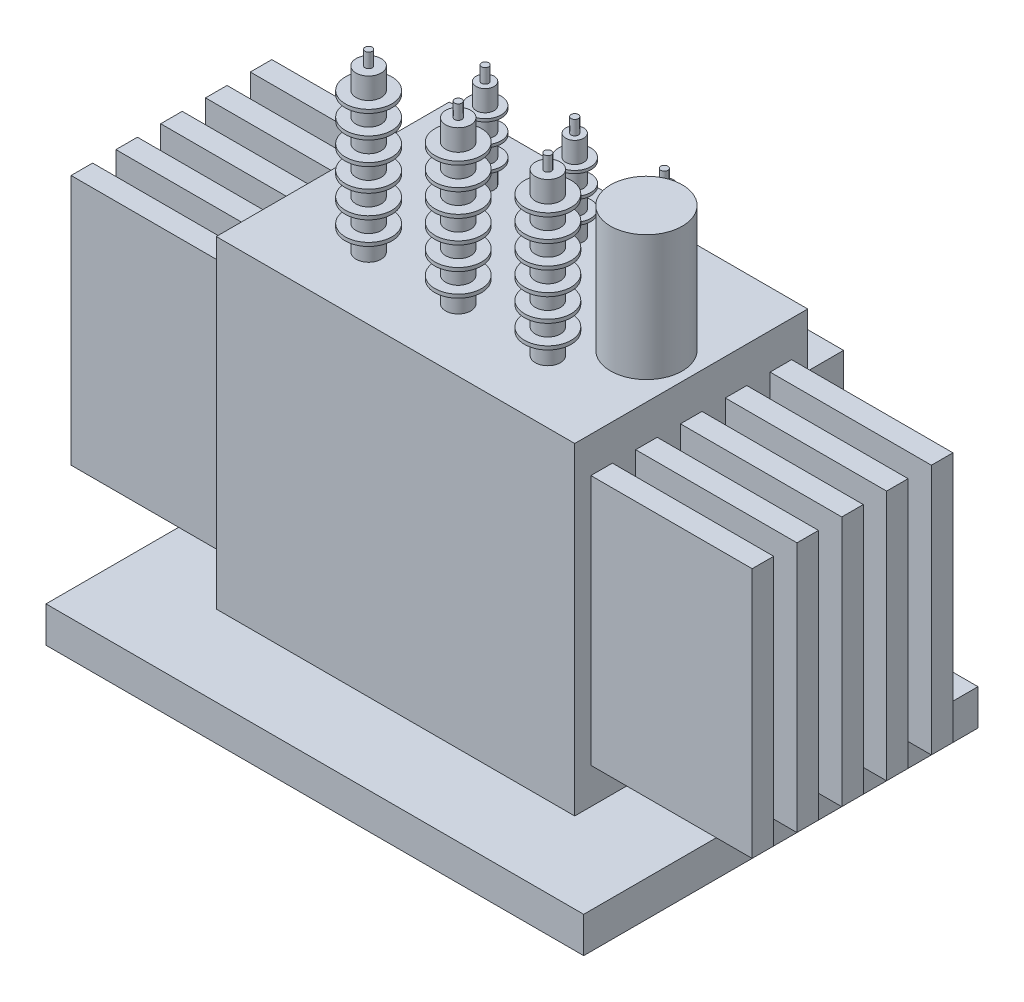
SolidWorks part; units mm, degrees
ref_plane "Front Plane" through (0, 0, 0) normal (0, 0, 1) x (1, 0, 0)
ref_plane "Top Plane" through (0, 0, 0) normal (0, 1, 0) x (1, 0, 0)
ref_plane "Right Plane" through (0, 0, 0) normal (1, 0, 0) x (0, 0, -1)
sketch "Sketch1" plane through (0, 0, 0) normal (0, 1, 0) x (1, 0, 0)
  line L1 (-1500, -1100) -> (1500, -1100)
  line L2 (-1500, -1100) -> (-1500, 1100)
  line L3 (-1500, 1100) -> (1500, 1100)
  line L4 (1500, -1100) -> (1500, 1100)
  line L5 (-1500, -1100) -> (1500, 1100) construction
  line L6 (-1500, 1100) -> (1500, -1100) construction
  point P0 (0, 0)
extrude "Pad" add sketch "Sketch1" along normal blind 200 separate body
sketch "Sketch2" plane through (0, 0, 0) normal (0, 1, 0) x (1, 0, 0)
  line L1 (-1000, -650) -> (1000, -650)
  line L2 (-1000, -650) -> (-1000, 650)
  line L3 (-1000, 650) -> (1000, 650)
  line L4 (1000, -650) -> (1000, 650)
  line L5 (-1000, -650) -> (1000, 650) construction
  line L6 (-1000, 650) -> (1000, -650) construction
  point P0 (0, 0)
extrude "Main tank" add sketch "Sketch2" along normal blind 1800 from offset 200 separate body
sketch "Sketch3" plane through (0, 0, 0) normal (0, 1, 0) x (1, 0, 0)
  line L1 (1000, 440) -> (1900, 440)
  line L2 (1000, 440) -> (1000, 560)
  line L3 (1000, 560) -> (1900, 560)
  line L4 (1900, 440) -> (1900, 560)
  line L5 (1000, 440) -> (1900, 560) construction
  line L6 (1000, 560) -> (1900, 440) construction
  point P0 (1450, 500)
extrude "Radiator +x 1" add sketch "Sketch3" along normal blind 1400 from offset 400 separate body
sketch "Sketch4" plane through (0, 0, 0) normal (0, 1, 0) x (1, 0, 0)
  line L1 (-1900, 440) -> (-1000, 440)
  line L2 (-1900, 440) -> (-1900, 560)
  line L3 (-1900, 560) -> (-1000, 560)
  line L4 (-1000, 440) -> (-1000, 560)
  line L5 (-1900, 440) -> (-1000, 560) construction
  line L6 (-1900, 560) -> (-1000, 440) construction
  point P0 (-1450, 500)
extrude "Radiator -x 1" add sketch "Sketch4" along normal blind 1400 from offset 400 separate body
sketch "Sketch5" plane through (0, 0, 0) normal (0, 1, 0) x (1, 0, 0)
  line L1 (1000, 190) -> (1900, 190)
  line L2 (1000, 190) -> (1000, 310)
  line L3 (1000, 310) -> (1900, 310)
  line L4 (1900, 190) -> (1900, 310)
  line L5 (1000, 190) -> (1900, 310) construction
  line L6 (1000, 310) -> (1900, 190) construction
  point P0 (1450, 250)
extrude "Radiator +x 2" add sketch "Sketch5" along normal blind 1400 from offset 400 separate body
sketch "Sketch6" plane through (0, 0, 0) normal (0, 1, 0) x (1, 0, 0)
  line L1 (-1900, 190) -> (-1000, 190)
  line L2 (-1900, 190) -> (-1900, 310)
  line L3 (-1900, 310) -> (-1000, 310)
  line L4 (-1000, 190) -> (-1000, 310)
  line L5 (-1900, 190) -> (-1000, 310) construction
  line L6 (-1900, 310) -> (-1000, 190) construction
  point P0 (-1450, 250)
extrude "Radiator -x 2" add sketch "Sketch6" along normal blind 1400 from offset 400 separate body
sketch "Sketch7" plane through (0, 0, 0) normal (0, 1, 0) x (1, 0, 0)
  line L1 (1000, -60) -> (1900, -60)
  line L2 (1000, -60) -> (1000, 60)
  line L3 (1000, 60) -> (1900, 60)
  line L4 (1900, -60) -> (1900, 60)
  line L5 (1000, -60) -> (1900, 60) construction
  line L6 (1000, 60) -> (1900, -60) construction
  point P0 (1450, 0)
extrude "Radiator +x 3" add sketch "Sketch7" along normal blind 1400 from offset 400 separate body
sketch "Sketch8" plane through (0, 0, 0) normal (0, 1, 0) x (1, 0, 0)
  line L1 (-1900, -60) -> (-1000, -60)
  line L2 (-1900, -60) -> (-1900, 60)
  line L3 (-1900, 60) -> (-1000, 60)
  line L4 (-1000, -60) -> (-1000, 60)
  line L5 (-1900, -60) -> (-1000, 60) construction
  line L6 (-1900, 60) -> (-1000, -60) construction
  point P0 (-1450, 0)
extrude "Radiator -x 3" add sketch "Sketch8" along normal blind 1400 from offset 400 separate body
sketch "Sketch9" plane through (0, 0, 0) normal (0, 1, 0) x (1, 0, 0)
  line L1 (1000, -310) -> (1900, -310)
  line L2 (1000, -310) -> (1000, -190)
  line L3 (1000, -190) -> (1900, -190)
  line L4 (1900, -310) -> (1900, -190)
  line L5 (1000, -310) -> (1900, -190) construction
  line L6 (1000, -190) -> (1900, -310) construction
  point P0 (1450, -250)
extrude "Radiator +x 4" add sketch "Sketch9" along normal blind 1400 from offset 400 separate body
sketch "Sketch10" plane through (0, 0, 0) normal (0, 1, 0) x (1, 0, 0)
  line L1 (-1900, -310) -> (-1000, -310)
  line L2 (-1900, -310) -> (-1900, -190)
  line L3 (-1900, -190) -> (-1000, -190)
  line L4 (-1000, -310) -> (-1000, -190)
  line L5 (-1900, -310) -> (-1000, -190) construction
  line L6 (-1900, -190) -> (-1000, -310) construction
  point P0 (-1450, -250)
extrude "Radiator -x 4" add sketch "Sketch10" along normal blind 1400 from offset 400 separate body
sketch "Sketch11" plane through (0, 0, 0) normal (0, 1, 0) x (1, 0, 0)
  line L1 (1000, -560) -> (1900, -560)
  line L2 (1000, -560) -> (1000, -440)
  line L3 (1000, -440) -> (1900, -440)
  line L4 (1900, -560) -> (1900, -440)
  line L5 (1000, -560) -> (1900, -440) construction
  line L6 (1000, -440) -> (1900, -560) construction
  point P0 (1450, -500)
extrude "Radiator +x 5" add sketch "Sketch11" along normal blind 1400 from offset 400 separate body
sketch "Sketch12" plane through (0, 0, 0) normal (0, 1, 0) x (1, 0, 0)
  line L1 (-1900, -560) -> (-1000, -560)
  line L2 (-1900, -560) -> (-1900, -440)
  line L3 (-1900, -440) -> (-1000, -440)
  line L4 (-1000, -560) -> (-1000, -440)
  line L5 (-1900, -560) -> (-1000, -440) construction
  line L6 (-1900, -440) -> (-1000, -560) construction
  point P0 (-1450, -500)
extrude "Radiator -x 5" add sketch "Sketch12" along normal blind 1400 from offset 400 separate body
sketch "Sketch13" plane through (0, 0, 0) normal (0, 1, 0) x (1, 0, 0)
  circle A0 centre (-500, -300) radius 70
extrude "Bushing HV 1" add sketch "Sketch13" along normal blind 900 from offset 2000 separate body
sketch "Sketch14" plane through (0, 0, 0) normal (0, 1, 0) x (1, 0, 0)
  circle A0 centre (-500, -300) radius 130
extrude "Shed HV 1 1" add sketch "Sketch14" along normal blind 20 from offset 2118.5714 separate body
sketch "Sketch15" plane through (0, 0, 0) normal (0, 1, 0) x (1, 0, 0)
  circle A0 centre (-500, -300) radius 130
extrude "Shed HV 1 2" add sketch "Sketch15" along normal blind 20 from offset 2247.1429 separate body
sketch "Sketch16" plane through (0, 0, 0) normal (0, 1, 0) x (1, 0, 0)
  circle A0 centre (-500, -300) radius 130
extrude "Shed HV 1 3" add sketch "Sketch16" along normal blind 20 from offset 2375.7143 separate body
sketch "Sketch17" plane through (0, 0, 0) normal (0, 1, 0) x (1, 0, 0)
  circle A0 centre (-500, -300) radius 130
extrude "Shed HV 1 4" add sketch "Sketch17" along normal blind 20 from offset 2504.2857 separate body
sketch "Sketch18" plane through (0, 0, 0) normal (0, 1, 0) x (1, 0, 0)
  circle A0 centre (-500, -300) radius 130
extrude "Shed HV 1 5" add sketch "Sketch18" along normal blind 20 from offset 2632.8571 separate body
sketch "Sketch19" plane through (0, 0, 0) normal (0, 1, 0) x (1, 0, 0)
  circle A0 centre (-500, -300) radius 130
extrude "Shed HV 1 6" add sketch "Sketch19" along normal blind 20 from offset 2761.4286 separate body
sketch "Sketch20" plane through (0, 0, 0) normal (0, 1, 0) x (1, 0, 0)
  circle A0 centre (-500, -300) radius 20
extrude "Terminal HV 1" add sketch "Sketch20" along normal blind 80 from offset 2900 separate body
sketch "Sketch21" plane through (0, 0, 0) normal (0, 1, 0) x (1, 0, 0)
  circle A0 centre (0, -300) radius 70
extrude "Bushing HV 2" add sketch "Sketch21" along normal blind 900 from offset 2000 separate body
sketch "Sketch22" plane through (0, 0, 0) normal (0, 1, 0) x (1, 0, 0)
  circle A0 centre (0, -300) radius 130
extrude "Shed HV 2 1" add sketch "Sketch22" along normal blind 20 from offset 2118.5714 separate body
sketch "Sketch23" plane through (0, 0, 0) normal (0, 1, 0) x (1, 0, 0)
  circle A0 centre (0, -300) radius 130
extrude "Shed HV 2 2" add sketch "Sketch23" along normal blind 20 from offset 2247.1429 separate body
sketch "Sketch24" plane through (0, 0, 0) normal (0, 1, 0) x (1, 0, 0)
  circle A0 centre (0, -300) radius 130
extrude "Shed HV 2 3" add sketch "Sketch24" along normal blind 20 from offset 2375.7143 separate body
sketch "Sketch25" plane through (0, 0, 0) normal (0, 1, 0) x (1, 0, 0)
  circle A0 centre (0, -300) radius 130
extrude "Shed HV 2 4" add sketch "Sketch25" along normal blind 20 from offset 2504.2857 separate body
sketch "Sketch26" plane through (0, 0, 0) normal (0, 1, 0) x (1, 0, 0)
  circle A0 centre (0, -300) radius 130
extrude "Shed HV 2 5" add sketch "Sketch26" along normal blind 20 from offset 2632.8571 separate body
sketch "Sketch27" plane through (0, 0, 0) normal (0, 1, 0) x (1, 0, 0)
  circle A0 centre (0, -300) radius 130
extrude "Shed HV 2 6" add sketch "Sketch27" along normal blind 20 from offset 2761.4286 separate body
sketch "Sketch28" plane through (0, 0, 0) normal (0, 1, 0) x (1, 0, 0)
  circle A0 centre (0, -300) radius 20
extrude "Terminal HV 2" add sketch "Sketch28" along normal blind 80 from offset 2900 separate body
sketch "Sketch29" plane through (0, 0, 0) normal (0, 1, 0) x (1, 0, 0)
  circle A0 centre (500, -300) radius 70
extrude "Bushing HV 3" add sketch "Sketch29" along normal blind 900 from offset 2000 separate body
sketch "Sketch30" plane through (0, 0, 0) normal (0, 1, 0) x (1, 0, 0)
  circle A0 centre (500, -300) radius 130
extrude "Shed HV 3 1" add sketch "Sketch30" along normal blind 20 from offset 2118.5714 separate body
sketch "Sketch31" plane through (0, 0, 0) normal (0, 1, 0) x (1, 0, 0)
  circle A0 centre (500, -300) radius 130
extrude "Shed HV 3 2" add sketch "Sketch31" along normal blind 20 from offset 2247.1429 separate body
sketch "Sketch32" plane through (0, 0, 0) normal (0, 1, 0) x (1, 0, 0)
  circle A0 centre (500, -300) radius 130
extrude "Shed HV 3 3" add sketch "Sketch32" along normal blind 20 from offset 2375.7143 separate body
sketch "Sketch33" plane through (0, 0, 0) normal (0, 1, 0) x (1, 0, 0)
  circle A0 centre (500, -300) radius 130
extrude "Shed HV 3 4" add sketch "Sketch33" along normal blind 20 from offset 2504.2857 separate body
sketch "Sketch34" plane through (0, 0, 0) normal (0, 1, 0) x (1, 0, 0)
  circle A0 centre (500, -300) radius 130
extrude "Shed HV 3 5" add sketch "Sketch34" along normal blind 20 from offset 2632.8571 separate body
sketch "Sketch35" plane through (0, 0, 0) normal (0, 1, 0) x (1, 0, 0)
  circle A0 centre (500, -300) radius 130
extrude "Shed HV 3 6" add sketch "Sketch35" along normal blind 20 from offset 2761.4286 separate body
sketch "Sketch36" plane through (0, 0, 0) normal (0, 1, 0) x (1, 0, 0)
  circle A0 centre (500, -300) radius 20
extrude "Terminal HV 3" add sketch "Sketch36" along normal blind 80 from offset 2900 separate body
sketch "Sketch37" plane through (0, 0, 0) normal (0, 1, 0) x (1, 0, 0)
  circle A0 centre (-500, 350) radius 50
extrude "Bushing LV 1" add sketch "Sketch37" along normal blind 500 from offset 2000 separate body
sketch "Sketch38" plane through (0, 0, 0) normal (0, 1, 0) x (1, 0, 0)
  circle A0 centre (-500, 350) radius 90
extrude "Shed LV 1 1" add sketch "Sketch38" along normal blind 16 from offset 2117 separate body
sketch "Sketch39" plane through (0, 0, 0) normal (0, 1, 0) x (1, 0, 0)
  circle A0 centre (-500, 350) radius 90
extrude "Shed LV 1 2" add sketch "Sketch39" along normal blind 16 from offset 2242 separate body
sketch "Sketch40" plane through (0, 0, 0) normal (0, 1, 0) x (1, 0, 0)
  circle A0 centre (-500, 350) radius 90
extrude "Shed LV 1 3" add sketch "Sketch40" along normal blind 16 from offset 2367 separate body
sketch "Sketch41" plane through (0, 0, 0) normal (0, 1, 0) x (1, 0, 0)
  circle A0 centre (-500, 350) radius 20
extrude "Terminal LV 1" add sketch "Sketch41" along normal blind 80 from offset 2500 separate body
sketch "Sketch42" plane through (0, 0, 0) normal (0, 1, 0) x (1, 0, 0)
  circle A0 centre (0, 350) radius 50
extrude "Bushing LV 2" add sketch "Sketch42" along normal blind 500 from offset 2000 separate body
sketch "Sketch43" plane through (0, 0, 0) normal (0, 1, 0) x (1, 0, 0)
  circle A0 centre (0, 350) radius 90
extrude "Shed LV 2 1" add sketch "Sketch43" along normal blind 16 from offset 2117 separate body
sketch "Sketch44" plane through (0, 0, 0) normal (0, 1, 0) x (1, 0, 0)
  circle A0 centre (0, 350) radius 90
extrude "Shed LV 2 2" add sketch "Sketch44" along normal blind 16 from offset 2242 separate body
sketch "Sketch45" plane through (0, 0, 0) normal (0, 1, 0) x (1, 0, 0)
  circle A0 centre (0, 350) radius 90
extrude "Shed LV 2 3" add sketch "Sketch45" along normal blind 16 from offset 2367 separate body
sketch "Sketch46" plane through (0, 0, 0) normal (0, 1, 0) x (1, 0, 0)
  circle A0 centre (0, 350) radius 20
extrude "Terminal LV 2" add sketch "Sketch46" along normal blind 80 from offset 2500 separate body
sketch "Sketch47" plane through (0, 0, 0) normal (0, 1, 0) x (1, 0, 0)
  circle A0 centre (500, 350) radius 50
extrude "Bushing LV 3" add sketch "Sketch47" along normal blind 500 from offset 2000 separate body
sketch "Sketch48" plane through (0, 0, 0) normal (0, 1, 0) x (1, 0, 0)
  circle A0 centre (500, 350) radius 90
extrude "Shed LV 3 1" add sketch "Sketch48" along normal blind 16 from offset 2117 separate body
sketch "Sketch49" plane through (0, 0, 0) normal (0, 1, 0) x (1, 0, 0)
  circle A0 centre (500, 350) radius 90
extrude "Shed LV 3 2" add sketch "Sketch49" along normal blind 16 from offset 2242 separate body
sketch "Sketch50" plane through (0, 0, 0) normal (0, 1, 0) x (1, 0, 0)
  circle A0 centre (500, 350) radius 90
extrude "Shed LV 3 3" add sketch "Sketch50" along normal blind 16 from offset 2367 separate body
sketch "Sketch51" plane through (0, 0, 0) normal (0, 1, 0) x (1, 0, 0)
  circle A0 centre (500, 350) radius 20
extrude "Terminal LV 3" add sketch "Sketch51" along normal blind 80 from offset 2500 separate body
sketch "Sketch52" plane through (0, 0, 0) normal (0, 1, 0) x (1, 0, 0)
  circle A0 centre (750, 0) radius 200
extrude "Conservator" add sketch "Sketch52" along normal blind 700 from offset 2000 separate body
sketch "Sketch53" plane through (0, 0, 0) normal (0, 1, 0) x (1, 0, 0)
  line L1 (200, 650) -> (800, 650)
  line L2 (200, 650) -> (200, 1050)
  line L3 (200, 1050) -> (800, 1050)
  line L4 (800, 650) -> (800, 1050)
  line L5 (200, 650) -> (800, 1050) construction
  line L6 (200, 1050) -> (800, 650) construction
  point P0 (500, 850)
extrude "Control cabinet" add sketch "Sketch53" along normal blind 1000 from offset 500 separate body
